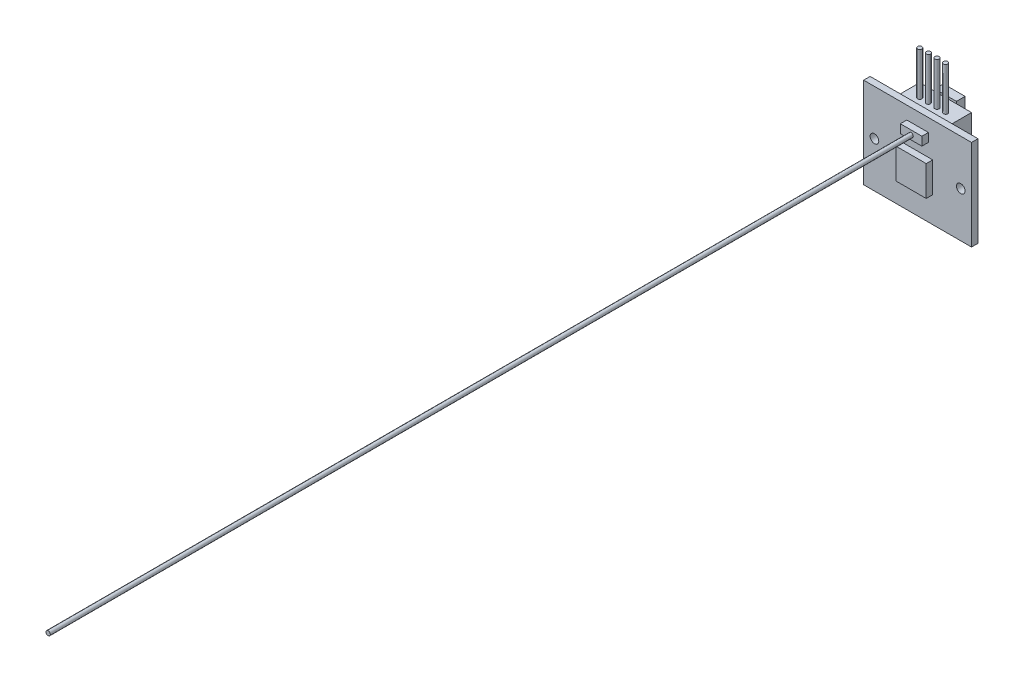
SolidWorks part; units mm, degrees
ref_plane "Plan de face" through (0, 0, 0) normal (0, 0, 1) x (1, 0, 0)
ref_plane "Plan de dessus" through (0, 0, 0) normal (0, 1, 0) x (1, 0, 0)
ref_plane "Plan de droite" through (0, 0, 0) normal (1, 0, 0) x (0, 0, -1)
sketch "Esquisse1" plane through (0, 0, 0) normal (0, 0, 1) x (1, 0, 0)
  line L0 (0, 10.5) -> (0, -10.5) construction
  line L1 (-12.5, -10.5) -> (12.5, -10.5)
  line L2 (-12.5, -10.5) -> (-12.5, 10.5)
  line L3 (-12.5, 10.5) -> (12.5, 10.5)
  line L4 (12.5, -10.5) -> (12.5, 10.5)
  circle A0 centre (-10, 0) radius 1
  circle A1 centre (10, 0) radius 1
  dimension "D3" = 20
  dimension "D4" = 2
  dimension "D1" = 25
  dimension "D2" = 21
extrude "Boss.-Extru.1" add sketch "Esquisse1" along normal blind 1.5
sketch "Esquisse2" plane through (0, 0, 0) normal (0, 0, -1) x (-1, 0, 0)
  line L1 (-6, 10) -> (6, 10)
  line L2 (-6, 10) -> (-6, 0)
  line L3 (-6, 0) -> (6, 0)
  line L4 (6, 10) -> (6, 0)
  dimension "D1" = 12
  dimension "D2" = 10
extrude "Boss.-Extru.2" add sketch "Esquisse2" along normal blind 5 separate body
sketch "Esquisse3" plane through (0, 0, 1.5) normal (0, 0, 1) x (1, 0, 0)
  line L0 (-12.5, 10.5) -> (-12.5, -10.5) construction
  line L1 (-2.5, 7.5) -> (2.5, 7.5)
  line L2 (-2.5, 7.5) -> (-2.5, 5.5)
  line L3 (-2.5, 5.5) -> (2.5, 5.5)
  line L4 (2.5, 7.5) -> (2.5, 5.5)
  line L5 (-3.5, 2.5) -> (3.5, 2.5)
  line L6 (-3.5, 2.5) -> (-3.5, -4.5)
  line L7 (-3.5, -4.5) -> (3.5, -4.5)
  line L8 (3.5, 2.5) -> (3.5, -4.5)
  line L9 (12.5, -10.5) -> (12.5, 10.5) construction
  line L10 (12.5, 10.5) -> (-12.5, 10.5) construction
  line L11 (-12.5, -10.5) -> (12.5, -10.5) construction
  dimension "D1" = 10
  dimension "D2" = 10
  dimension "D3" = 5
  dimension "D4" = 3
  dimension "D5" = 16
  dimension "D6" = 2
  dimension "D7" = 9
  dimension "D8" = 9
  dimension "D9" = 7
  dimension "D10" = 7
  dimension "D11" = 6
  dimension "D12" = 3
extrude "Boss.-Extru.3" add sketch "Esquisse3" along normal blind 1.5 separate body
sketch "Esquisse4" plane through (0, 0, -5) normal (0, 0, -1) x (-1, 0, 0)
  line L0 (-12.5, 10.5) -> (12.5, 10.5) construction
  line L1 (-2.5, 10.5) -> (2.5, 10.5)
  line L2 (-2.5, 10.5) -> (-2.5, 2.5)
  line L3 (-2.5, 2.5) -> (2.5, 2.5)
  line L4 (2.5, 10.5) -> (2.5, 2.5)
  point P6 (0, 2.5)
  dimension "D1" = 5
  dimension "D2" = 8
extrude "Boss.-Extru.4" add sketch "Esquisse4" along normal blind 2
sketch "Esquisse5" plane through (0, 10, 0) normal (0, 1, 0) x (1, 0, 0)
  line L0 (-6, 0) -> (6, 0) construction
  circle A0 centre (-3, 2) radius 0.5
  circle A1 centre (-1, 2) radius 0.5
  circle A2 centre (1, 2) radius 0.5
  circle A3 centre (3, 2) radius 0.5
  dimension "D1" = 4
  dimension "D2" = 6
  dimension "D3" = 3
  dimension "D4" = 1
  dimension "D5" = 2
extrude "Boss.-Extru.5" add sketch "Esquisse5" along normal blind 10 separate body
sketch "Esquisse6" plane through (0, 0, 3) normal (0, 0, 1) x (1, 0, 0)
  line L0 (2.5, 7.5) -> (-2.5, 5.5) construction
  circle A0 centre (0, 6.5) radius 0.5
  dimension "D1" = 1
extrude "Boss.-Extru.6" add sketch "Esquisse6" along normal blind 200 separate body
